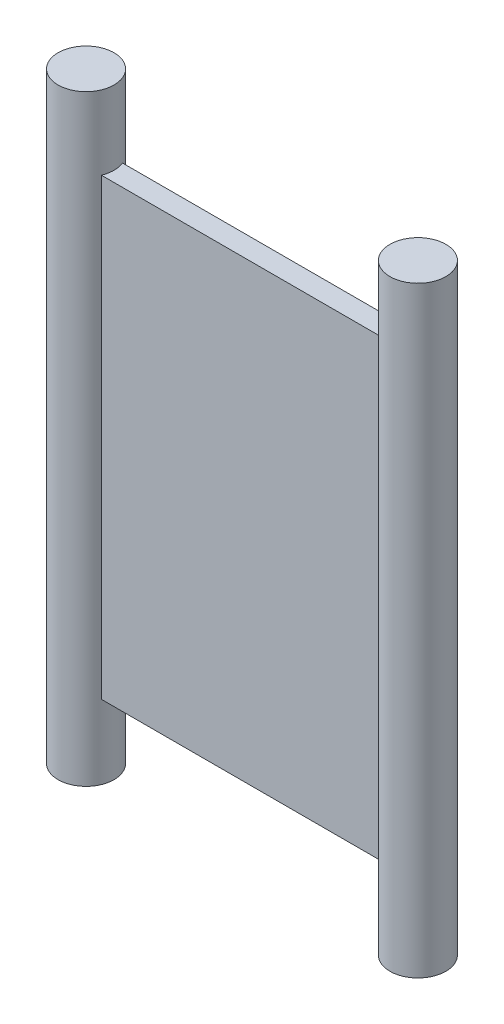
SolidWorks part; units mm, degrees
ref_plane "Front Plane" through (0, 0, 0) normal (0, 0, 1) x (1, 0, 0)
ref_plane "Top Plane" through (0, 0, 0) normal (0, 1, 0) x (1, 0, 0)
ref_plane "Right Plane" through (0, 0, 0) normal (1, 0, 0) x (0, 0, -1)
sketch "Sketch1" plane through (0, 0, 0) normal (0, 1, 0) x (1, 0, 0)
  line L1 (7.86, 0.5) -> (-7.86, 0.5)
  line L2 (7.86, 0.5) -> (7.86, -0.5)
  line L3 (7.86, -0.5) -> (-7.86, -0.5)
  line L4 (-7.86, 0.5) -> (-7.86, -0.5)
  line L5 (7.86, 0.5) -> (-7.86, -0.5) construction
  line L6 (7.86, -0.5) -> (-7.86, 0.5) construction
  point P0 (0, 0)
  dimension "D1" = 15.72
  dimension "D3" = 1
extrude "Boss-Extrude1" add sketch "Sketch1" along normal blind 21.5
ref_plane "Plane1" through (0, 10.75, 0) normal (0, 1, 0) x (1, 0, 0)
sketch "Sketch2" plane through (0, 10.75, 0) normal (0, 1, 0) x (1, 0, 0)
  line L0 (7.86, -0.5) -> (7.86, 0.5) construction
  line L1 (-7.86, 0.5) -> (-7.86, -0.5) construction
  line L2 (7.86, -0.5) -> (7.86, 0.5) construction
  line L3 (-7.86, 0.5) -> (-7.86, -0.5) construction
  circle A0 centre (-7.86, 0) radius 1.325
  circle A1 centre (7.86, 0) radius 1.325
  dimension "D1" = 2.65
extrude "Boss-Extrude2" add sketch "Sketch2" along normal mid plane 28.5
